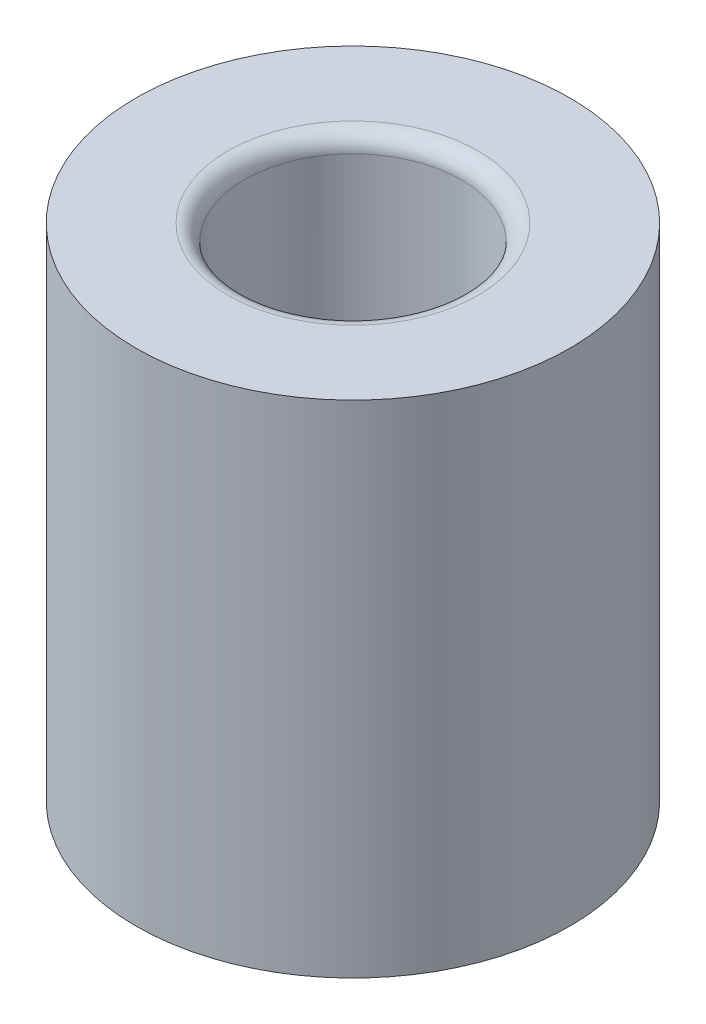
SolidWorks part; units mm, degrees
material "AISI 1020"
ref_plane "Plano superior" through (0, 0, 0) normal (0, 0, 1) x (1, 0, 0)
ref_plane "Plano frontal" through (0, 0, 0) normal (0, 1, 0) x (1, 0, 0)
ref_plane "Plano direito" through (0, 0, 0) normal (1, 0, 0) x (0, 0, -1)
sketch "Esboço1" plane through (0, 0, 0) normal (0, 1, 0) x (1, 0, 0)
  circle A0 centre (0, 0) radius 6.5
  dimension "D1" = 13
extrude "Ressalto-extrusão1" add sketch "Esboço1" along normal blind 15
sketch "Esboço4" plane through (0, 0, 0) normal (0, -1, 0) x (1, 0, 0)
  circle A0 centre (0, 0) radius 4.5
  dimension "D1" = 9
extrude "Corte-extrusão1" cut sketch "Esboço4" against normal blind 3.1
sketch "Esboço5" plane through (0, 3.1, 0) normal (0, -1, 0) x (1, 0, 0)
  circle A0 centre (0, 0) radius 3.25
  dimension "D1" = 6.5
extrude "Corte-extrusão2" cut sketch "Esboço5" against normal through all
chamfer "Chanfro1" distance 0.5 angle 45 1 edges at (0, 0, -4.5)
fillet "Filete1" radius 0.5 1 edges at (0, 3.1, -3.25)
fillet "Filete2" radius 0.5 1 edges at (0, 15, -3.25)
